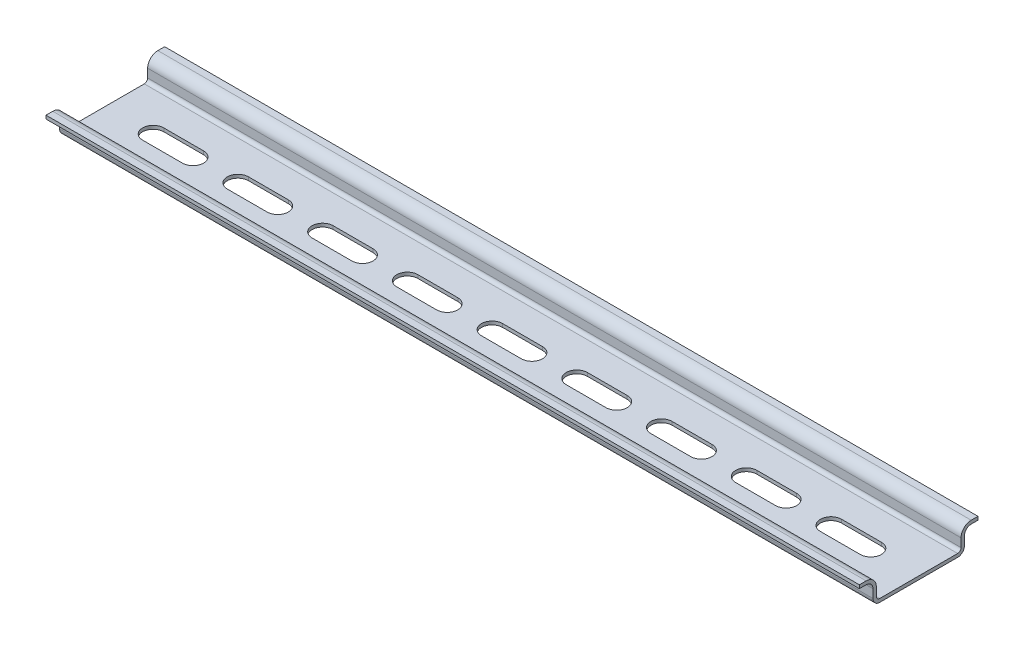
SolidWorks part; units mm, degrees
ref_plane "Front Plane" through (0, 0, 0) normal (0, 0, 1) x (1, 0, 0)
ref_plane "Top Plane" through (0, 0, 0) normal (0, 1, 0) x (1, 0, 0)
ref_plane "Right Plane" through (0, 0, 0) normal (1, 0, 0) x (0, 0, -1)
sketch "Sketch1" plane through (0, 0, 0) normal (1, 0, 0) x (0, 0, -1)
  line L0 (0, 0) -> (0, 18.2344) construction
  line L1 (0, 0) -> (26.621, 0) construction
  line L2 (-11.5, 0) -> (11.5, 0)
  line L3 (13.5, 2) -> (13.5, 4.5)
  line L4 (15.5, 6.5) -> (17.5, 6.5)
  line L5 (-13.5, 2) -> (-13.5, 4.5)
  line L6 (-15.5, 6.5) -> (-17.5, 6.5)
  arc A0 (13.5, 2) -> (11.5, 0) centre (11.5, 2) cw
  arc A1 (15.5, 6.5) -> (13.5, 4.5) centre (15.5, 4.5) ccw
  arc A2 (-13.5, 2) -> (-11.5, 0) centre (-11.5, 2) ccw
  arc A3 (-15.5, 6.5) -> (-13.5, 4.5) centre (-15.5, 4.5) cw
  point P9 (13.5, 0)
  dimension "D1" = 2
  dimension "D3" = 2
  dimension "D2" = 6.5
  dimension "D4" = 35
  dimension "D5" = 27
extrude "Extrude-Thin1" add sketch "Sketch1" along normal blind 120 and the other way blind 120 thin thin type one direction wall 1
sketch "Sketch2" plane through (0, 0, 0) normal (0, -1, 0) x (1, 0, 0)
  line L0 (0, 6.6969) -> (0, 0) construction
  line L1 (0, 0) -> (9.9599, 0) construction
  line L2 (-5.875, 3.125) -> (5.875, 3.125)
  line L3 (-5.875, -3.125) -> (5.875, -3.125)
  arc A0 (5.875, 3.125) -> (5.875, -3.125) centre (5.875, 0) cw
  arc A1 (-5.875, 3.125) -> (-5.875, -3.125) centre (-5.875, 0) ccw
  point P6 (0, 3.125)
  point P12 (0, -3.125)
  dimension "D2" = 11.75
  dimension "D1" = 6.25
extrude "Cut-Extrude1" cut sketch "Sketch2" against normal up to next
pattern_linear "LPattern1" count 5 spacing 25 along (1, 0, 0) count 5 spacing 25 along (-1, 0, 0) of "Cut-Extrude1"
